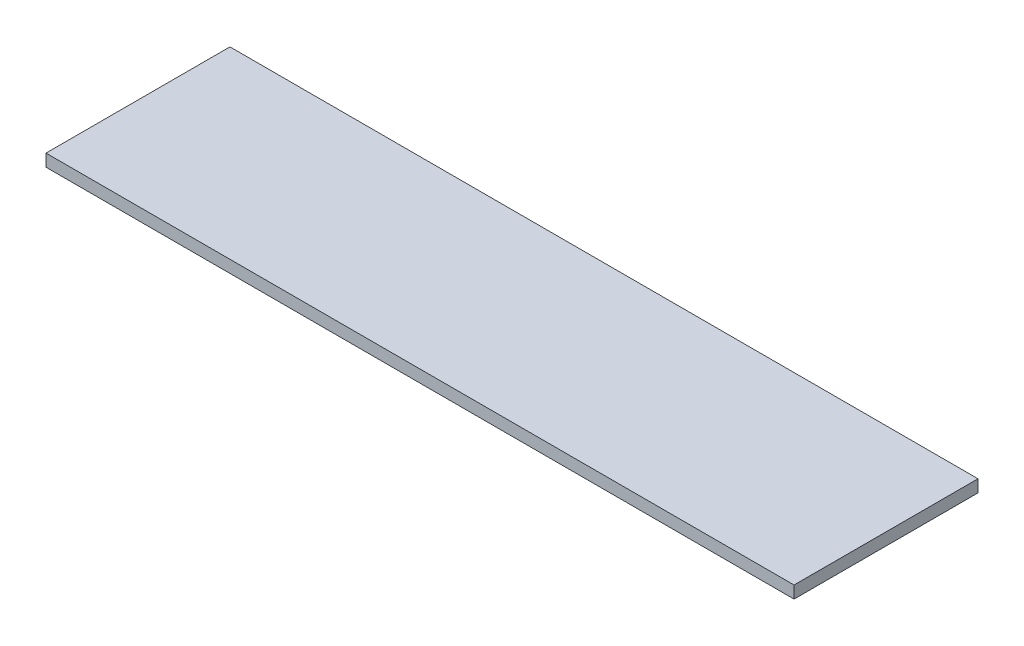
SolidWorks part; units mm, degrees
ref_plane "Front Plane" through (0, 0, 0) normal (0, 0, 1) x (1, 0, 0)
ref_plane "Top Plane" through (0, 0, 0) normal (0, 1, 0) x (1, 0, 0)
ref_plane "Right Plane" through (0, 0, 0) normal (1, 0, 0) x (0, 0, -1)
sketch "Sketch1" plane through (0, 0, 0) normal (0, 1, 0) x (1, 0, 0)
  line L1 (0, 0) -> (774.7, 0)
  line L2 (0, 0) -> (0, 190.5)
  line L3 (0, 190.5) -> (774.7, 190.5)
  line L4 (774.7, 0) -> (774.7, 190.5)
  dimension "D1" = 774.7
  dimension "D2" = 190.5
extrude "Boss-Extrude1" add sketch "Sketch1" along normal blind 12.7
